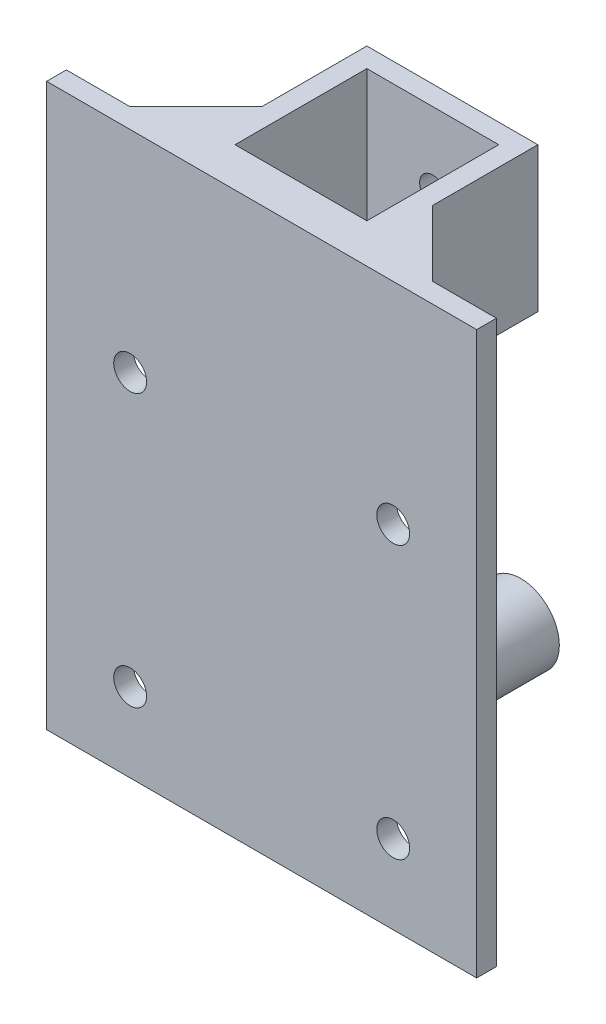
SolidWorks part; units mm, degrees
ref_plane "Спереди" through (0, 0, 0) normal (0, 0, 1) x (1, 0, 0)
ref_plane "Сверху" through (0, 0, 0) normal (0, 1, 0) x (1, 0, 0)
ref_plane "Справа" through (0, 0, 0) normal (1, 0, 0) x (0, 0, -1)
sketch "Эскиз1" plane through (0, 0, 0) normal (0, 0, 1) x (1, 0, 0)
  line L0 (-65.4, 53.4) -> (0, 53.4) construction
  line L1 (0, 0) -> (-65.4, 0)
  line L2 (0, 0) -> (0, 85.4)
  line L3 (0, 85.4) -> (-65.4, 85.4)
  line L4 (-65.4, 0) -> (-65.4, 85.4)
  line L5 (-32.7, 85.4) -> (-32.7, 0) construction
  circle A0 centre (-52.7, 53.4) radius 2.5
  circle A2 centre (-12.7, 53.4) radius 2.5
  circle A3 centre (-12.7, 12) radius 2.5
  circle A4 centre (-52.7, 12) radius 2.5
  point P19 (0, 0)
  point P20 (0, 0)
  dimension "D4" = 5
  dimension "D5" = 20
  dimension "D7" = 12
  dimension "D8" = 5
  dimension "D9" = 5
  dimension "D10" = 41.4
  dimension "D1" = 65.4
  dimension "D2" = 85.4
  dimension "D3" = 12
  dimension "D6" = 32
  dimension "D11" = 41.4
extrude "каретка" add sketch "Эскиз1" along normal blind 3
sketch "Эскиз2" plane through (0, 0, 0) normal (0, 0, -1) x (-1, 0, 0)
  line L0 (0, 85.4) -> (65.4, 85.4) construction
  line L1 (19.7, 85.4) -> (45.7, 85.4)
  line L2 (19.7, 85.4) -> (19.7, 63.4)
  line L3 (19.7, 63.4) -> (45.7, 63.4)
  line L4 (45.7, 85.4) -> (45.7, 63.4)
  line L5 (32.7, 85.4) -> (32.7, 0) construction
  line L6 (65.4, 0) -> (0, 0) construction
  point P10 (32.7, 85.4)
  dimension "D1" = 22
  dimension "D2" = 26
extrude "крепеж для направляющей" add sketch "Эскиз2" along normal blind 26
sketch "Эскиз3" plane through (0, 63.4, 0) normal (0, -1, 0) x (1, 0, 0)
  line L0 (-45.7, -13) -> (-19.7, -13) construction
  line L1 (-42.725, -2.975) -> (-22.675, -2.975)
  line L2 (-42.725, -2.975) -> (-42.725, -23.025)
  line L3 (-42.725, -23.025) -> (-22.675, -23.025)
  line L4 (-22.675, -2.975) -> (-22.675, -23.025)
  line L5 (-45.7, -26) -> (-45.7, 0) construction
  line L6 (-19.7, -26) -> (-19.7, 0) construction
  line L7 (-42.725, -13) -> (-22.675, -13) construction
  point P12 (-32.7, -13)
  point P13 (-32.7, -13)
  dimension "D1" = 20.05
  dimension "D2" = 20.05
extrude "дырка в крепеже для направляющей" cut sketch "Эскиз3" against normal through all
sketch "Эскиз4" plane through (0, 0, 0) normal (0, 0, -1) x (-1, 0, 0)
  line L0 (12.7, 53.4) -> (12.7, 12) construction
  line L1 (52.7, 53.4) -> (52.7, 12) construction
  circle A1 centre (52.7, 32.7) radius 2
  point P6 (52.7, 32.7)
  dimension "D1" = 4
sketch "Эскиз8" plane through (0, 0, 0) normal (0, 0, -1) x (-1, 0, 0)
  line L0 (12.7, 53.4) -> (12.7, 12) construction
  line L1 (0, 0) -> (0, 85.4) construction
  line L2 (65.4, 0) -> (0, 0) construction
  circle A0 centre (10.7, 32.7) radius 5.8726
  point P2 (0, 0)
  dimension "D1" = 11.7451
  dimension "D2" = 10.7
  dimension "D3" = 32.7
extrude "Бобышка-Вытянуть1" add sketch "Эскиз8" along normal blind 14.4
extrude "Бобышка-Вытянуть3" add sketch "Эскиз4" along normal blind 14.4 contours A1
sketch "Эскиз12" plane through (0, 0, 0) normal (0, 0, -1) x (-1, 0, 0)
  line L0 (65.4, 85.4) -> (65.4, 0) construction
  line L1 (52.7, 34.7) -> (52.7, 30.7) construction
  line L2 (65.4, 0) -> (0, 0) construction
  circle A0 centre (54.7, 32.7) radius 5
  circle A1 centre (52.7, 32.7) radius 2 construction
  circle A2 centre (52.7, 32.7) radius 2 construction
  point P2 (0, 0)
  point P3 (0, 0)
  point P4 (0, 0)
  point P5 (0, 0)
  dimension "D1" = 10
  dimension "D2" = 10.7
  dimension "D3" = 32.7
extrude "Бобышка-Вытянуть5" add sketch "Эскиз12" along normal blind 21 contours A0
sketch "Эскиз13" plane through (0, 0, -21) normal (0, 0, -1) x (-1, 0, 0)
  circle A0 centre (54.7, 32.7) radius 2
  dimension "D1" = 4
extrude "Вырез-Вытянуть1" cut sketch "Эскиз13" against normal blind 6.6
sketch "Эскиз14" plane through (0, 0, -14.4) normal (0, 0, -1) x (-1, 0, 0)
  line L1 (10.7, 38.5726) -> (10.7, 26.8274) construction
  circle A0 centre (10.7, 32.7) radius 2
  circle A3 centre (10.7, 32.7) radius 5.8726 construction
  circle A4 centre (10.7, 32.7) radius 5.8726 construction
  point P13 (10.7, 32.7)
  dimension "D1" = 4
extrude "Вырез-Вытянуть3" cut sketch "Эскиз14" against normal blind 8 contours A0
chamfer "Фаска1" distance 10 angle 45 1 edges at (-45.7, 74.4, 0)
chamfer "Фаска2" distance 10 angle 45 1 edges at (-19.7, 74.4, 0)
sketch "Эскиз15" plane through (0, 0, -26) normal (0, 0, -1) x (-1, 0, 0)
  line L0 (19.7, 85.4) -> (45.7, 63.4) construction
  circle A0 centre (32.7, 74.4) radius 2
  dimension "D1" = 4
extrude "Вырез-Вытянуть4" cut sketch "Эскиз15" against normal blind 8
